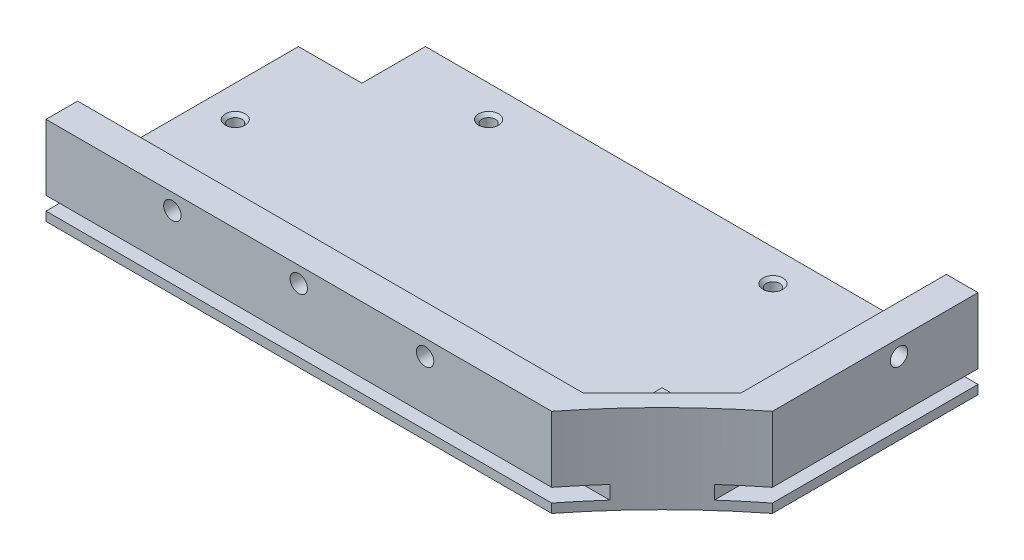
SolidWorks part; units mm, degrees
ref_plane "Front Plane" through (0, 0, 0) normal (0, 0, 1) x (1, 0, 0)
ref_plane "Top Plane" through (0, 0, 0) normal (0, 1, 0) x (1, 0, 0)
ref_plane "Right Plane" through (0, 0, 0) normal (1, 0, 0) x (0, 0, -1)
sketch "Sketch1" plane through (0, 0, 0) normal (0, 1, 0) x (1, 0, 0)
  line L0 (0, 0) -> (0, 650)
  line L1 (0, 650) -> (650, 650)
  line L2 (650, 650) -> (650, 0)
  line L3 (650, 0) -> (0, 0)
  dimension "D1" = 650
  dimension "D2" = 650
extrude "Boss-Extrude1" add sketch "Sketch1" along normal blind 8
sketch "Sketch3" plane through (0, 0, 0) normal (0, 0, 1) x (1, 0, 0)
  line L0 (325, 8) -> (325, 43.7071) construction
  line L1 (0, 8) -> (650, 8) construction
  line L2 (300, 43.7071) -> (350, 43.7071)
  line L3 (300, 43.7071) -> (265, 8)
  line L4 (265, 8) -> (385, 8)
  line L5 (385, 8) -> (350, 43.7071)
  point P7 (325, 43.7071)
  dimension "D1" = 50
  dimension "D2" = 50
  dimension "D3" = 50
  dimension "D4" = 120
extrude "Boss-Extrude2" add sketch "Sketch3" against normal blind 650
sketch "Sketch4" plane through (0, 0, 0) normal (0, 0, 1) x (1, 0, 0)
  line L0 (265, 8) -> (385, 8) construction
  circle A0 centre (325, 22) radius 11
  dimension "D1" = 14
extrude "Cut-Extrude2" cut sketch "Sketch4" against normal through all both and the other way through all
sketch "Sketch2" plane through (0, 8, 0) normal (0, 1, 0) x (1, 0, 0)
  line L0 (0, 650) -> (0, 0) construction
  line L1 (650, 650) -> (385, 650) construction
  circle A0 centre (325, 325) radius 210
  dimension "D3" = 420
  dimension "D1" = 325
  dimension "D2" = 325
extrude "Cut-Extrude1" cut sketch "Sketch2" against normal through all both and the other way through all
sketch "Sketch5" plane through (0, 0, 0) normal (0, 0, 1) x (1, 0, 0)
  line L0 (300, 43.7071) -> (350, 43.7071)
  line L1 (265, 8) -> (385, 8) construction
  line L2 (300, 8) -> (300, 28)
  line L3 (300, 8) -> (350, 8)
  line L4 (350, 8) -> (350, 28)
  line L5 (350, 28) -> (365.3961, 28)
  line L6 (385, 8) -> (350, 43.7071) construction
  line L7 (365.3961, 28) -> (350, 43.7071)
  line L8 (300, 28) -> (284.6039, 28)
  line L9 (300, 43.7071) -> (265, 8) construction
  line L10 (284.6039, 28) -> (300, 43.7071)
extrude "Cut-Extrude3" cut sketch "Sketch5" against normal blind 110 and the other way through all
sketch "Sketch6" plane through (0, 0, -650) normal (0, 0, -1) x (-1, 0, 0)
  line L0 (-265, 8) -> (-385, 8) construction
  line L1 (-350, 43.7071) -> (-300, 43.7071)
  line L2 (-300, 8) -> (-300, 28)
  line L3 (-300, 28) -> (-284.6039, 28)
  line L4 (-300, 43.7071) -> (-265, 8) construction
  line L5 (-284.6039, 28) -> (-300, 43.7071)
  line L6 (-350, 8) -> (-350, 28)
  line L7 (-350, 28) -> (-365.3961, 28)
  line L8 (-365.3961, 28) -> (-350, 43.7071)
  line L9 (-350, 8) -> (-300, 8)
extrude "Cut-Extrude4" cut sketch "Sketch6" against normal blind 110
sketch "Sketch7" plane through (0, 8, 0) normal (0, 1, 0) x (1, 0, 0)
  line L1 (325, 325) -> (325, 455) construction
  line L2 (325, 325) -> (325, 195) construction
  line L3 (325, 325) -> (455, 325) construction
  line L4 (325, 325) -> (195, 325) construction
  line L9 (325, 455) -> (455, 455) construction
  line L10 (455, 455) -> (455, 195) construction
  line L11 (455, 195) -> (195, 195) construction
  line L12 (195, 195) -> (195, 455) construction
  line L13 (195, 455) -> (325, 455) construction
  line L14 (195, 455) -> (195, 489.9242)
  line L15 (195, 489.9242) -> (195, 650)
  line L16 (265, 650) -> (0, 650) construction
  line L17 (195, 455) -> (160.0758, 455)
  line L18 (160.0758, 455) -> (0, 455)
  line L19 (0, 650) -> (0, 0) construction
  line L20 (0, 455) -> (-70.8389, 472.4621)
  line L21 (-70.8389, 472.4621) -> (-70.8389, 686.5445)
  line L22 (-70.8389, 686.5445) -> (167.4782, 686.5445)
  line L23 (167.4782, 686.5445) -> (195, 650)
  arc A0 (265, 526.2461) -> (265, 123.7539) centre (325, 325) ccw construction
  dimension "D1" = 130
  dimension "D2" = 130
  dimension "D3" = 130
  dimension "D4" = 130
extrude "Cut-Extrude5" cut sketch "Sketch7" against normal through all both and the other way through all flip side to cut
sketch "Sketch8" plane through (0, 0, -650) normal (0, 0, -1) x (-1, 0, 0)
  line L0 (-195, 8) -> (-195, 28)
  line L1 (-195, 28) -> (-185, 28)
  line L2 (-185, 28) -> (-185, 17)
  line L3 (-185, 17) -> (-175, 8)
  line L4 (-195, 8) -> (0, 8) construction
  line L5 (-175, 8) -> (-195, 8)
  dimension "D1" = 10
  dimension "D2" = 20
  dimension "D3" = 11
  dimension "D4" = 20
extrude "Boss-Extrude3" add sketch "Sketch8" against normal blind 160.08
sketch "Sketch10" plane through (0, 0, 0) normal (-1, 0, 0) x (0, 0, 1)
  line L0 (-455, 8) -> (-455, 28)
  line L1 (-455, 28) -> (-465, 28)
  line L2 (-465, 28) -> (-465, 17)
  line L3 (-465, 17) -> (-475, 8)
  line L4 (-650, 8) -> (-455, 8) construction
  line L5 (-475, 8) -> (-455, 8)
  dimension "D1" = 10
  dimension "D2" = 20
  dimension "D3" = 11
  dimension "D4" = 20
extrude "Boss-Extrude4" add sketch "Sketch10" against normal blind 160.08
sketch "Sketch21" plane through (0, 0, 0) normal (-1, 0, 0) x (0, 0, 1)
  line L0 (-455, 7.15) -> (-465, 7.15)
  line L1 (-455, 0) -> (-455, 28) construction
  line L2 (-465, 7.15) -> (-465, 2.85)
  line L3 (-465, 2.85) -> (-455, 2.85)
  line L4 (-455, 2.85) -> (-455, 7.15)
  line L5 (-650, 0) -> (-455, 0) construction
  dimension "D1" = 2.85
  dimension "D2" = 4.3
extrude "Cut-Extrude10" cut sketch "Sketch21" against normal through all
sketch "Sketch22" plane through (0, 0, -650) normal (0, 0, -1) x (-1, 0, 0)
  line L0 (-195, 7.15) -> (-185, 7.15)
  line L1 (-195, 0) -> (-195, 28) construction
  line L2 (-185, 7.15) -> (-185, 2.85)
  line L3 (-185, 2.85) -> (-195, 2.85)
  line L4 (-195, 2.85) -> (-195, 7.15)
  line L5 (-195, 0) -> (0, 0) construction
  dimension "D1" = 2.85
  dimension "D2" = 4.3
  dimension "D3" = 10
extrude "Cut-Extrude11" cut sketch "Sketch22" against normal through all
sketch "Sketch12" plane through (0, 8, 0) normal (0, 1, 0) x (1, 0, 0)
  line L0 (0, 0) -> (0, 650) construction
  line L1 (0, 650) -> (650, 650) construction
  line L2 (650, 650) -> (0, 0) construction
  circle A0 centre (325, 325) radius 210
sketch "Sketch23" plane through (0, 0, -489.92) normal (0, 0, 1) x (1, 0, 0)
  line L3 (194.9946, 8) -> (195, 28)
  line L4 (195, 28) -> (160.08, 28)
  line L5 (160.08, 28) -> (160.08, 8)
  line L6 (160.08, 8) -> (194.9946, 8)
extrude "Boss-Extrude5" add sketch "Sketch23" along normal blind 60
extrude "Cut-Extrude6" cut sketch "Sketch12" against normal through all both and the other way through all
sketch "Sketch26" plane through (0, 28, 0) normal (0, 1, 0) x (1, 0, 0)
  line L0 (185, 489.92) -> (160.08, 489.92)
  line L1 (160.08, 489.92) -> (160.08, 465)
  line L2 (160.08, 465) -> (185, 489.92)
extrude "Cut-Extrude14" cut sketch "Sketch26" against normal blind 11
sketch "Sketch27" plane through (185, 0, 0) normal (-1, 0, 0) x (0, 0, 1)
  line L0 (-650, 17) -> (-650, 28) construction
  line L1 (-489.92, 28) -> (-650, 28) construction
  circle A0 centre (-610, 23) radius 2.2
  circle A1 centre (-570, 23) radius 2.2
  circle A2 centre (-530, 23) radius 2.75
  dimension "D1" = 40
  dimension "D7" = 5.5
  dimension "D2" = 40
  dimension "D3" = 40
  dimension "D4" = 5
  dimension "D5" = 5
  dimension "D6" = 5
extrude "Cut-Extrude15" cut sketch "Sketch27" against normal blind 11
sketch "Sketch28" plane through (0, 0, -465) normal (0, 0, -1) x (-1, 0, 0)
  line L0 (0, 28) -> (0, 17) construction
  line L1 (-160.08, 28) -> (0, 28) construction
  circle A0 centre (-120, 23) radius 2.75
  circle A1 centre (-80, 23) radius 2.75
  circle A2 centre (-40, 23) radius 2.75
  dimension "D1" = 5.5
  dimension "D2" = 5.5
  dimension "D3" = 5.5
  dimension "D4" = 40
  dimension "D5" = 40
  dimension "D6" = 40
  dimension "D7" = 5
  dimension "D8" = 5
  dimension "D9" = 5
extrude "Cut-Extrude16" cut sketch "Sketch28" against normal blind 11
sketch "Sketch29" plane through (0, 8, 0) normal (0, 1, 0) x (1, 0, 0)
  line L0 (0, 650) -> (20, 650)
  line L1 (175, 650) -> (0, 650) construction
  line L2 (20, 650) -> (20, 630)
  line L3 (20, 630) -> (0, 630)
  line L4 (0, 650) -> (0, 475) construction
  line L5 (0, 630) -> (0, 650)
extrude "Cut-Extrude17" cut sketch "Sketch29" against normal blind 10
sketch "Sketch30" plane through (0, 8, 0) normal (0, 1, 0) x (1, 0, 0)
  line L0 (195, 650) -> (195, 555)
  line L1 (195, 489.9242) -> (195, 650) construction
  line L2 (195, 555) -> (0, 555)
  line L3 (0, 630) -> (0, 475) construction
  line L4 (195, 650) -> (0, 650)
  line L5 (0, 650) -> (0, 555)
extrude "Cut-Extrude18" cut sketch "Sketch30" against normal through all both and the other way through all
sketch "Sketch31" plane through (0, 8, 0) normal (0, 1, 0) x (1, 0, 0)
  line L0 (0, 555) -> (20.1, 555)
  line L1 (175, 555) -> (0, 555) construction
  line L2 (20.1, 555) -> (20.1, 534.9)
  line L3 (20.1, 534.9) -> (0, 534.9)
  line L4 (0, 555) -> (0, 475) construction
  line L5 (0, 555) -> (0, 534.9)
  dimension "D1" = 20.1
  dimension "D2" = 20.1
extrude "Cut-Extrude19" cut sketch "Sketch31" against normal through all both and the other way through all
sketch "Sketch32" plane through (0, 8, 0) normal (0, 1, 0) x (1, 0, 0)
  line L0 (175, 555) -> (20.1, 555) construction
  line L1 (0, 534.9) -> (0, 475) construction
  line L2 (20.1, 534.9) -> (0, 534.9) construction
  line L3 (20.1, 555) -> (20.1, 534.9) construction
  circle A0 centre (50.1, 545) radius 2.15
  circle A1 centre (140.1, 545) radius 2.15
  circle A2 centre (10, 504.9) radius 2.15
  dimension "D1" = 4.3
  dimension "D2" = 4.3
  dimension "D3" = 4.3
  dimension "D4" = 10
  dimension "D5" = 10
  dimension "D6" = 10
  dimension "D7" = 30
  dimension "D8" = 30
  dimension "D9" = 90
extrude "Cut-Extrude20" cut sketch "Sketch32" against normal blind 10
chamfer "Chamfer1" distance 1 angle 45 3 edges at (140.1, 8, -542.85) (50.1, 8, -542.85) (10, 8, -502.75)
